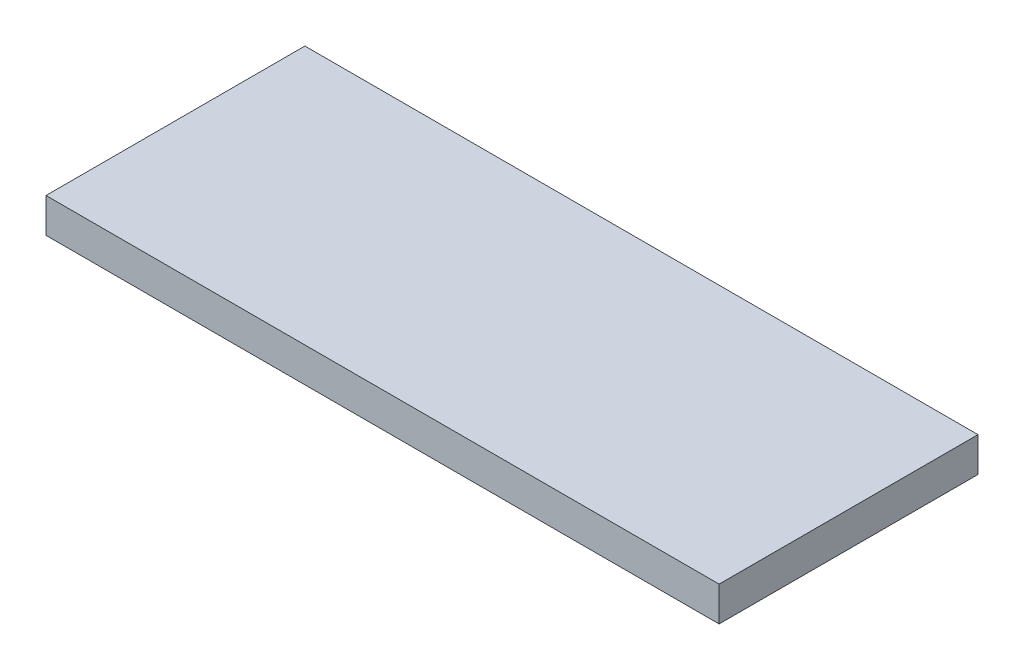
SolidWorks part; units mm, degrees
ref_plane "前基準面" through (0, 0, 0) normal (0, 0, 1) x (1, 0, 0)
ref_plane "上基準面" through (0, 0, 0) normal (0, 1, 0) x (1, 0, 0)
ref_plane "右基準面" through (0, 0, 0) normal (1, 0, 0) x (0, 0, -1)
sketch "草圖2" plane through (0, 0, 0) normal (0, 1, 0) x (1, 0, 0)
  line L0 (-9.75, -3.75) -> (9.75, -3.75)
  line L1 (-9.75, -3.75) -> (-9.75, 3.75)
  line L2 (-9.75, 3.75) -> (9.75, 3.75)
  line L3 (9.75, -3.75) -> (9.75, 3.75)
  line L4 (-9.75, -3.75) -> (9.75, 3.75) construction
  line L5 (-9.75, 3.75) -> (9.75, -3.75) construction
  point P0 (0, 0)
  dimension "D1" = 19.5
  dimension "D2" = 7.5
extrude "伸長1" add sketch "草圖2" along normal blind 1
